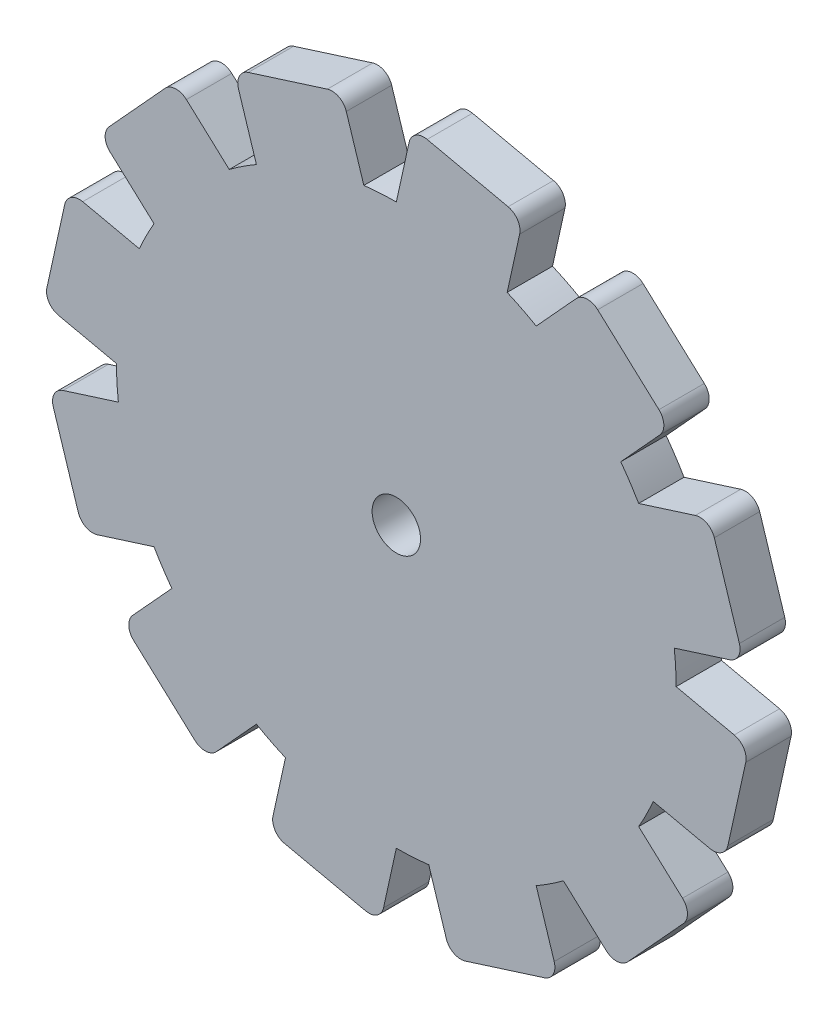
SolidWorks part; units mm, degrees
material "ABS PC"
ref_plane "Front Plane" through (0, 0, 0) normal (0, 0, 1) x (1, 0, 0)
ref_plane "Top Plane" through (0, 0, 0) normal (0, 1, 0) x (1, 0, 0)
ref_plane "Right Plane" through (0, 0, 0) normal (1, 0, 0) x (0, 0, -1)
sketch "Sketch1" plane through (0, 0, 0) normal (0, 0, 1) x (1, 0, 0)
  circle A0 centre (0, 0) radius 18.5
  dimension "D1" = 37
extrude "Boss-Extrude1" add sketch "Sketch1" along normal blind 3
sketch "Sketch2" plane through (0, 0, 3) normal (0, 0, 1) x (1, 0, 0)
  line L0 (0, 34.3429) -> (0, -28.9804) construction
  line L27 (12.0107, -18.5514) -> (7.5743, -20.8575)
  line L30 (5.6902, -21.355) -> (0.7582, -22.1773)
  line L61 (0, 18.5) -> (0.8451, 22.3404)
  line L62 (2.0366, 23.1021) -> (7.3906, 21.924)
  line L63 (17.4264, 13.8787) -> (14.8397, 11.0469)
  line L64 (9.25, 16.0215) -> (11.902, 18.9248)
  line L65 (13.3148, 18.9887) -> (17.3624, 15.2914)
  line L66 (22.031, 3.3061) -> (18.375, 2.147)
  line L67 (16.0215, 9.25) -> (19.7699, 10.4383)
  line L68 (21.0253, 9.7873) -> (22.682, 4.5615)
  line L69 (20.7324, -8.1523) -> (16.9867, -7.3281)
  line L70 (18.5, 0) -> (22.3404, -0.8451)
  line L71 (23.1021, -2.0366) -> (21.924, -7.3906)
  line L72 (13.8787, -17.4264) -> (11.0469, -14.8397)
  line L73 (16.0215, -9.25) -> (18.9248, -11.902)
  line L74 (18.9887, -13.3148) -> (15.2914, -17.3624)
  line L75 (3.3061, -22.031) -> (2.147, -18.375)
  line L76 (9.25, -16.0215) -> (10.4383, -19.7699)
  line L77 (9.7873, -21.0253) -> (4.5615, -22.682)
  line L78 (-8.1523, -20.7324) -> (-7.3281, -16.9867)
  line L79 (0, -18.5) -> (-0.8451, -22.3404)
  line L80 (-2.0366, -23.1021) -> (-7.3906, -21.924)
  line L81 (-17.4264, -13.8787) -> (-14.8397, -11.0469)
  line L82 (-9.25, -16.0215) -> (-11.902, -18.9248)
  line L83 (-13.3148, -18.9887) -> (-17.3624, -15.2914)
  line L84 (-22.031, -3.3061) -> (-18.375, -2.147)
  line L85 (-16.0215, -9.25) -> (-19.7699, -10.4383)
  line L86 (-21.0253, -9.7873) -> (-22.682, -4.5615)
  line L87 (-20.7324, 8.1523) -> (-16.9867, 7.3281)
  line L88 (-18.5, 0) -> (-22.3404, 0.8451)
  line L89 (-23.1021, 2.0366) -> (-21.924, 7.3906)
  line L90 (-13.8787, 17.4264) -> (-11.0469, 14.8397)
  line L91 (-16.0215, 9.25) -> (-18.9248, 11.902)
  line L92 (-18.9887, 13.3148) -> (-15.2914, 17.3624)
  line L93 (-3.3061, 22.031) -> (-2.147, 18.375)
  line L94 (-9.25, 16.0215) -> (-10.4383, 19.7699)
  line L95 (-9.7873, 21.0253) -> (-4.5615, 22.682)
  line L99 (8.1523, 20.7324) -> (7.3281, 16.9867)
  circle A0 centre (0, 0) radius 18.5 construction
  arc A26 (6.9, -20.6445) -> (7.5743, -20.8575) centre (7.3437, -20.4139) ccw
  arc A29 (0.1828, -21.7663) -> (0.7582, -22.1773) centre (0.676, -21.6841) ccw
  arc A31 (6.1011, -20.7796) -> (5.6902, -21.355) centre (5.6079, -20.8618) cw
  arc A62 (17.4264, 13.8787) -> (17.3624, 15.2914) centre (16.688, 14.5531) ccw
  arc A63 (9.25, 16.0215) -> (14.8397, 11.0469) centre (0, 0) cw
  arc A64 (13.3148, 18.9887) -> (11.902, 18.9248) centre (12.6404, 18.2504) ccw
  arc A65 (22.031, 3.3061) -> (22.682, 4.5615) centre (21.7288, 4.2593) ccw
  arc A66 (16.0215, 9.25) -> (18.375, 2.147) centre (0, 0) cw
  arc A67 (21.0253, 9.7873) -> (19.7699, 10.4383) centre (20.0721, 9.4851) ccw
  arc A68 (20.7324, -8.1523) -> (21.924, -7.3906) centre (20.9473, -7.1757) ccw
  arc A69 (18.5, 0) -> (16.9867, -7.3281) centre (0, 0) cw
  arc A70 (23.1021, -2.0366) -> (22.3404, -0.8451) centre (22.1255, -1.8217) ccw
  arc A71 (13.8787, -17.4264) -> (15.2914, -17.3624) centre (14.5531, -16.688) ccw
  arc A72 (16.0215, -9.25) -> (11.0469, -14.8397) centre (0, 0) cw
  arc A73 (18.9887, -13.3148) -> (18.9248, -11.902) centre (18.2504, -12.6404) ccw
  arc A74 (3.3061, -22.031) -> (4.5615, -22.682) centre (4.2593, -21.7288) ccw
  arc A75 (9.25, -16.0215) -> (2.147, -18.375) centre (0, 0) cw
  arc A76 (9.7873, -21.0253) -> (10.4383, -19.7699) centre (9.4851, -20.0721) ccw
  arc A77 (-8.1523, -20.7324) -> (-7.3906, -21.924) centre (-7.1757, -20.9473) ccw
  arc A78 (0, -18.5) -> (-7.3281, -16.9867) centre (0, 0) cw
  arc A79 (0, 18.5) -> (7.3281, 16.9867) centre (0, 0) cw
  arc A80 (8.1523, 20.7324) -> (7.3906, 21.924) centre (7.1757, 20.9473) ccw
  arc A81 (2.0366, 23.1021) -> (0.8451, 22.3404) centre (1.8217, 22.1255) ccw
  arc A82 (-2.0366, -23.1021) -> (-0.8451, -22.3404) centre (-1.8217, -22.1255) ccw
  arc A83 (-17.4264, -13.8787) -> (-17.3624, -15.2914) centre (-16.688, -14.5531) ccw
  arc A84 (-9.25, -16.0215) -> (-14.8397, -11.0469) centre (0, 0) cw
  arc A85 (-13.3148, -18.9887) -> (-11.902, -18.9248) centre (-12.6404, -18.2504) ccw
  arc A86 (-22.031, -3.3061) -> (-22.682, -4.5615) centre (-21.7288, -4.2593) ccw
  arc A87 (-16.0215, -9.25) -> (-18.375, -2.147) centre (0, 0) cw
  arc A88 (-21.0253, -9.7873) -> (-19.7699, -10.4383) centre (-20.0721, -9.4851) ccw
  arc A89 (-20.7324, 8.1523) -> (-21.924, 7.3906) centre (-20.9473, 7.1757) ccw
  arc A90 (-18.5, 0) -> (-16.9867, 7.3281) centre (0, 0) cw
  arc A91 (-23.1021, 2.0366) -> (-22.3404, 0.8451) centre (-22.1255, 1.8217) ccw
  arc A92 (-13.8787, 17.4264) -> (-15.2914, 17.3624) centre (-14.5531, 16.688) ccw
  arc A93 (-16.0215, 9.25) -> (-11.0469, 14.8397) centre (0, 0) cw
  arc A94 (-18.9887, 13.3148) -> (-18.9248, 11.902) centre (-18.2504, 12.6404) ccw
  arc A95 (-3.3061, 22.031) -> (-4.5615, 22.682) centre (-4.2593, 21.7288) ccw
  arc A96 (-9.25, 16.0215) -> (-2.147, 18.375) centre (0, 0) cw
  arc A97 (-9.7873, 21.0253) -> (-10.4383, 19.7699) centre (-9.4851, 20.0721) ccw
  point P115 (0, 0)
  dimension "D1" = 90
  dimension "D4" = 12
  dimension "D2" = 1
  dimension "D3" = 0.5
  dimension "D5" = 23
extrude "Boss-Extrude2" add sketch "Sketch2" against normal blind 3
sketch "Sketch3" plane through (0, 0, 3) normal (0, 0, 1) x (1, 0, 0)
  circle A0 centre (0, 0) radius 1.6
  dimension "D1" = 3.2
extrude "Cut-Extrude1" cut sketch "Sketch3" against normal blind 3
